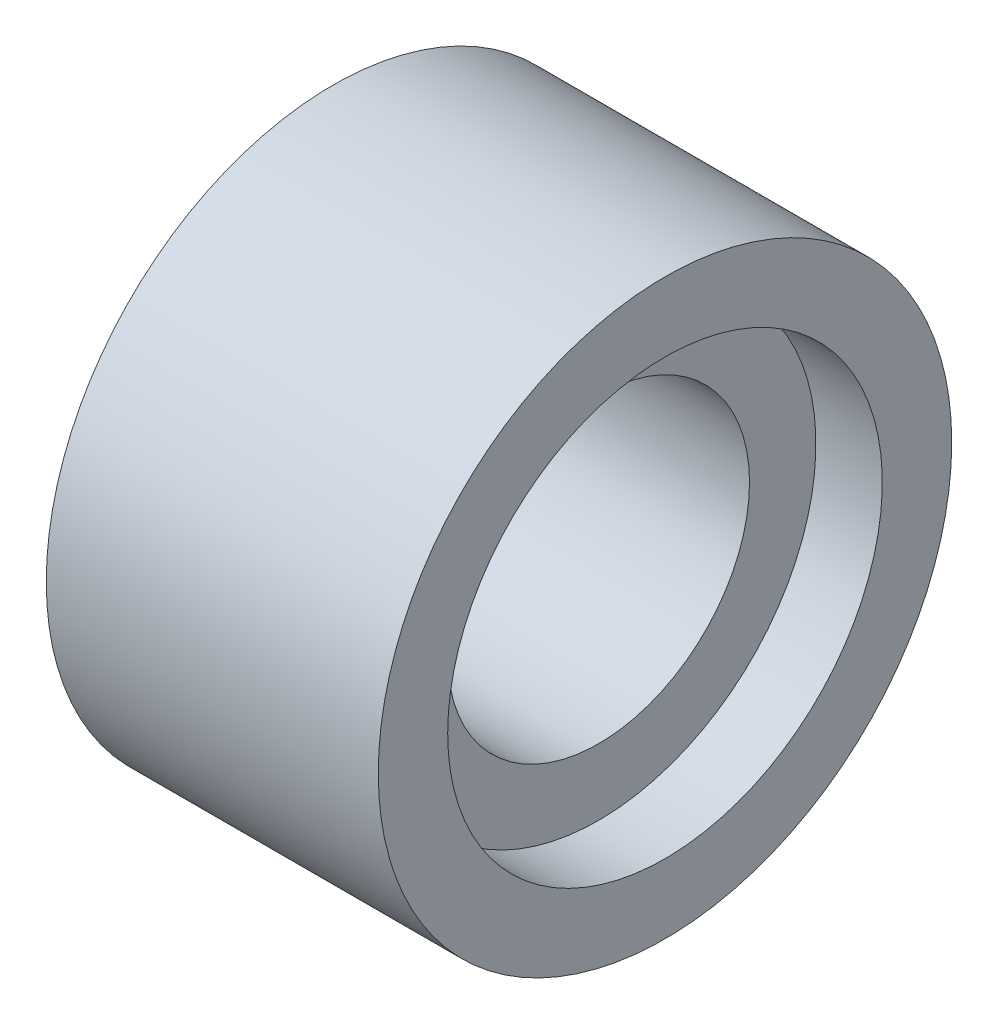
SolidWorks part; units mm, degrees
ref_plane "Plan1" through (0, 0, 0) normal (0, 0, 1) x (1, 0, 0)
ref_plane "Plan2" through (0, 0, 0) normal (0, 1, 0) x (1, 0, 0)
ref_plane "Plan3" through (0, 0, 0) normal (1, 0, 0) x (0, 0, -1)
sketch "Esquisse1" plane through (0, 0, 0) normal (0, 0, 1) x (1, 0, 0)
  line L0 (0, 7.3341) -> (0, 9.6341)
  line L1 (0, 9.6341) -> (11, 9.6341)
  line L2 (11, 9.6341) -> (11, 7.3341)
  line L8 (-12.5747, 0.1341) -> (48.4041, 0.1341) construction
  line L9 (0, 7.3341) -> (2.2, 7.3341)
  line L10 (2.2, 7.3341) -> (2.2, 5.1341)
  line L11 (2.2, 5.1341) -> (8.8, 5.1341)
  line L12 (8.8, 5.1341) -> (8.8, 7.3341)
  line L13 (8.8, 7.3341) -> (11, 7.3341)
  dimension "D1" = 7.2
  dimension "D2" = 2.2
  dimension "D3" = 2.2
  dimension "D4" = 11
  dimension "D5" = 9.5
  dimension "D6" = 5
revolve "Base-Révolution" add sketch "Esquisse1" angle 360 about L8
